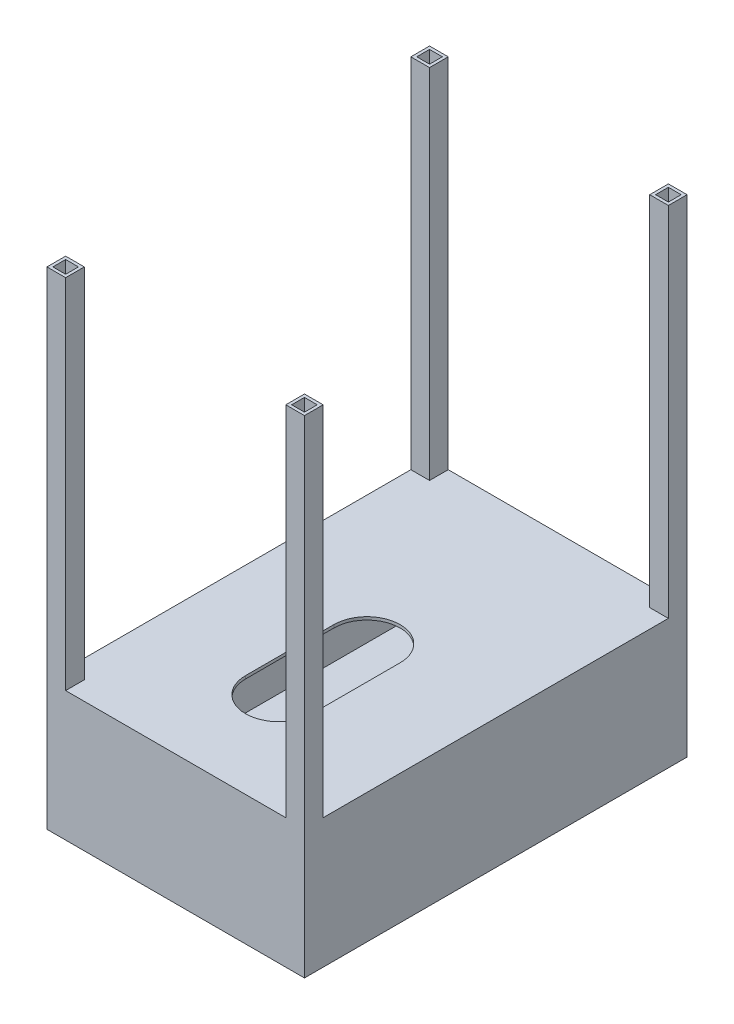
SolidWorks part; units mm, degrees
material "1060 Alloy"
ref_plane "Front Plane" through (0, 0, 0) normal (0, 0, 1) x (1, 0, 0)
ref_plane "Top Plane" through (0, 0, 0) normal (0, 1, 0) x (1, 0, 0)
ref_plane "Right Plane" through (0, 0, 0) normal (1, 0, 0) x (0, 0, -1)
sketch "Sketch1" plane through (0, 0, 0) normal (0, 1, 0) x (1, 0, 0)
  line L1 (-87.5, 130) -> (87.5, 130)
  line L2 (-87.5, 130) -> (-87.5, -130)
  line L3 (-87.5, -130) -> (87.5, -130)
  line L4 (87.5, 130) -> (87.5, -130)
  line L5 (-87.5, 130) -> (87.5, -130) construction
  line L6 (-87.5, -130) -> (87.5, 130) construction
  point P0 (0, 0)
  dimension "D1" = 175
  dimension "D2" = 260
extrude "Boss-Extrude1" add sketch "Sketch1" along normal blind 3
sketch "Sketch2" plane through (0, 0, 0) normal (0, -1, 0) x (1, 0, 0)
  line L0 (-87.5, -130) -> (87.5, 130)
  point P3 (0, 0)
sketch "Sketch3" plane through (0, 3, 0) normal (0, 1, 0) x (1, 0, 0)
  line L0 (87.5, 130) -> (-87.5, 130) construction
  line L1 (-87.5, 130) -> (-74.8, 130)
  line L2 (-87.5, 130) -> (-87.5, 117.3)
  line L3 (-87.5, 117.3) -> (-74.8, 117.3)
  line L4 (-74.8, 130) -> (-74.8, 117.3)
  line L5 (-87.5, 130) -> (-74.8, 117.3) construction
  line L6 (-87.5, 117.3) -> (-74.8, 130) construction
  line L7 (-87.5, 130) -> (-87.5, -130) construction
  point P0 (-81.15, 123.65)
  dimension "D1" = 12.7
extrude "Extrude-Thin1" add sketch "Sketch3" along normal blind 328 thin
mirror "Mirror1" about plane through (0, 0, 0) normal (1, 0, 0) of "Extrude-Thin1"
mirror "Mirror2" about plane through (0, 0, 0) normal (0, 0, 1) of "Mirror1", "Extrude-Thin1"
sketch "Sketch4" plane through (0, 3, 0) normal (0, 1, 0) x (1, 0, 0)
  line L0 (-87.5, 130) -> (87.5, -130)
  point P3 (0, 0)
sketch "Sketch5" plane through (0, 3, 0) normal (0, 1, 0) x (1, 0, 0)
  line L1 (-87.5, 130) -> (87.5, 130)
  line L2 (-87.5, 130) -> (-87.5, -130)
  line L3 (-87.5, -130) -> (87.5, -130)
  line L4 (87.5, 130) -> (87.5, -130)
  line L5 (-87.5, 130) -> (87.5, -130) construction
  line L6 (-87.5, -130) -> (87.5, 130) construction
  line L8 (74.8, 130) -> (-74.8, 130) construction
  line L9 (-87.5, 117.3) -> (-87.5, -117.3) construction
  line L10 (87.5, -117.3) -> (87.5, 117.3) construction
  line L11 (-74.8, -130) -> (74.8, -130) construction
  point P0 (0, 0)
extrude "Extrude-Thin2" add sketch "Sketch5" along normal blind 83 thin
sketch "Sketch6" plane through (0, 86, 0) normal (0, 1, 0) x (1, 0, 0)
  line L0 (74.8, 130) -> (-74.8, 130) construction
  line L1 (-87.5, 130) -> (87.5, 130)
  line L2 (-87.5, 130) -> (-87.5, -130)
  line L3 (-87.5, -130) -> (87.5, -130)
  line L4 (87.5, 130) -> (87.5, -130)
  line L5 (-87.5, 130) -> (87.5, -130) construction
  line L6 (-87.5, -130) -> (87.5, 130) construction
  line L7 (-74.8, -130) -> (74.8, -130) construction
  line L8 (87.5, -117.3) -> (87.5, 117.3) construction
  line L9 (-87.5, 117.3) -> (-87.5, -117.3) construction
  point P0 (0, 0)
extrude "Boss-Extrude2" add sketch "Sketch6" along normal blind 2
sketch "Sketch8" plane through (0, 3, 0) normal (0, 1, 0) x (1, 0, 0)
  line L0 (-22.5, 0) -> (-22.5, -60)
  line L1 (22.5, 0) -> (22.5, -60)
  circle A0 centre (0, 0) radius 22.5
  circle A1 centre (0, -60) radius 22.5
  dimension "D1" = 45
  dimension "D2" = 60
extrude "Cut-Extrude1" cut sketch "Sketch8" along normal through all contours A1 | A1 L1 A0 L0 | A0
sketch "Sketch9" plane through (0, 0, 0) normal (0, -1, 0) x (1, 0, 0)
  line L0 (-15, -105) -> (15, -105)
  line L1 (-15, -120) -> (15, -120)
  line L2 (0, -120) -> (0, -130) construction
  line L3 (87.5, -130) -> (-87.5, -130) construction
  circle A0 centre (-15, -112.5) radius 7.5
  circle A1 centre (15, -112.5) radius 7.5
  point P10 (0, 0)
  point P13 (0, 0)
  dimension "D2" = 15
  dimension "D1" = 30
  dimension "D3" = 10
extrude "Cut-Extrude2" cut sketch "Sketch9" against normal up to surface (3 mm away) contours A0 | A1 L0 A0 L1 | A1 up to face at (0, 3, 0)
